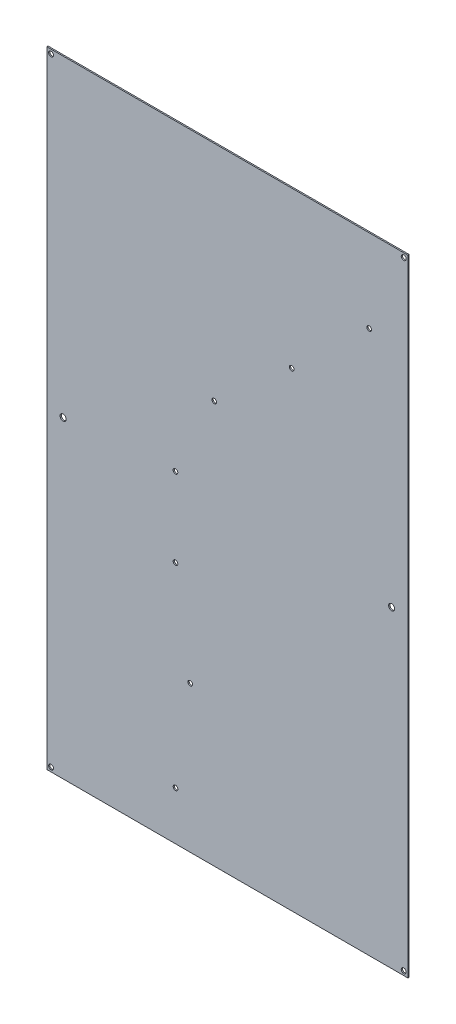
SolidWorks part; units mm, degrees
ref_plane "Front Plane" through (0, 0, 0) normal (0, 0, 1) x (1, 0, 0)
ref_plane "Top Plane" through (0, 0, 0) normal (0, 1, 0) x (1, 0, 0)
ref_plane "Right Plane" through (0, 0, 0) normal (1, 0, 0) x (0, 0, -1)
sketch "Sketch1" plane through (0, 0, 0) normal (0, 0, 1) x (1, 0, 0)
  line L1 (-109.8476, 958.0814) -> (-109.8476, 108.0814) construction
  line L2 (360.1524, 958.0814) -> (360.1524, 108.0814) construction
  line L3 (360.1524, 919.9815) -> (-109.8476, 919.9815) construction
  line L4 (-109.8476, 108.0814) -> (360.1524, 108.0814) construction
  line L5 (-109.8476, 919.9815) -> (-109.8476, 108.0814) construction
  line L6 (360.1524, 919.9815) -> (360.1524, 108.0814) construction
  line L7 (360.1524, 919.9815) -> (-109.8476, 919.9815) construction
  line L8 (-107.8476, 110.0814) -> (358.1524, 110.0814)
  line L9 (358.1524, 917.9815) -> (358.1524, 110.0814)
  line L10 (358.1524, 917.9815) -> (-107.8476, 917.9815)
  line L11 (-107.8476, 917.9815) -> (-107.8476, 110.0814)
  circle A0 centre (-102.4054, 115.5224) radius 3.175 construction
  circle A1 centre (352.7102, 115.5224) radius 3.175 construction
  circle A2 centre (-102.4054, 912.5404) radius 3.175 construction
  circle A3 centre (352.7102, 912.5404) radius 3.175 construction
  circle A4 centre (-102.4054, 115.5224) radius 3.175
  circle A5 centre (352.7102, 115.5224) radius 3.175
  circle A6 centre (-102.4054, 912.5404) radius 3.175
  circle A7 centre (352.7102, 912.5404) radius 3.175
  circle A8 centre (-86.8936, 514.0314) radius 3.9687 construction
  circle A9 centre (337.1984, 514.0314) radius 3.9688 construction
  circle A10 centre (-86.8936, 514.0314) radius 3.9687
  circle A11 centre (337.1984, 514.0314) radius 3.9688
  circle A12 centre (308.1524, 811.1555) radius 3
  circle A13 centre (208.1524, 716.5835) radius 3
  circle A14 centre (108.1524, 630.0785) radius 3
  circle A15 centre (58.1524, 526.3935) radius 3
  circle A17 centre (77.1524, 298.9815) radius 3
  circle A19 centre (58.1864, 172.6705) radius 3
  circle A20 centre (58.1864, 424.3745) radius 3
  point P40 (232.1524, 398.9815)
  dimension "D1" = 126
  dimension "D2" = 519
  dimension "D3" = 412.174
  dimension "D4" = 317.602
  dimension "D5" = 231.097
  dimension "D6" = 50
  dimension "D7" = 150
  dimension "D8" = 250
  dimension "D9" = 127.412
  dimension "D10" = 300
  dimension "D11" = 25.393
  dimension "D12" = 299.966
  dimension "D13" = 299.966
  dimension "D14" = 226.311
  dimension "D15" = 100
  dimension "D16" = 155
extrude "Boss-Extrude1" add sketch "Sketch1" along normal blind 1.6002
